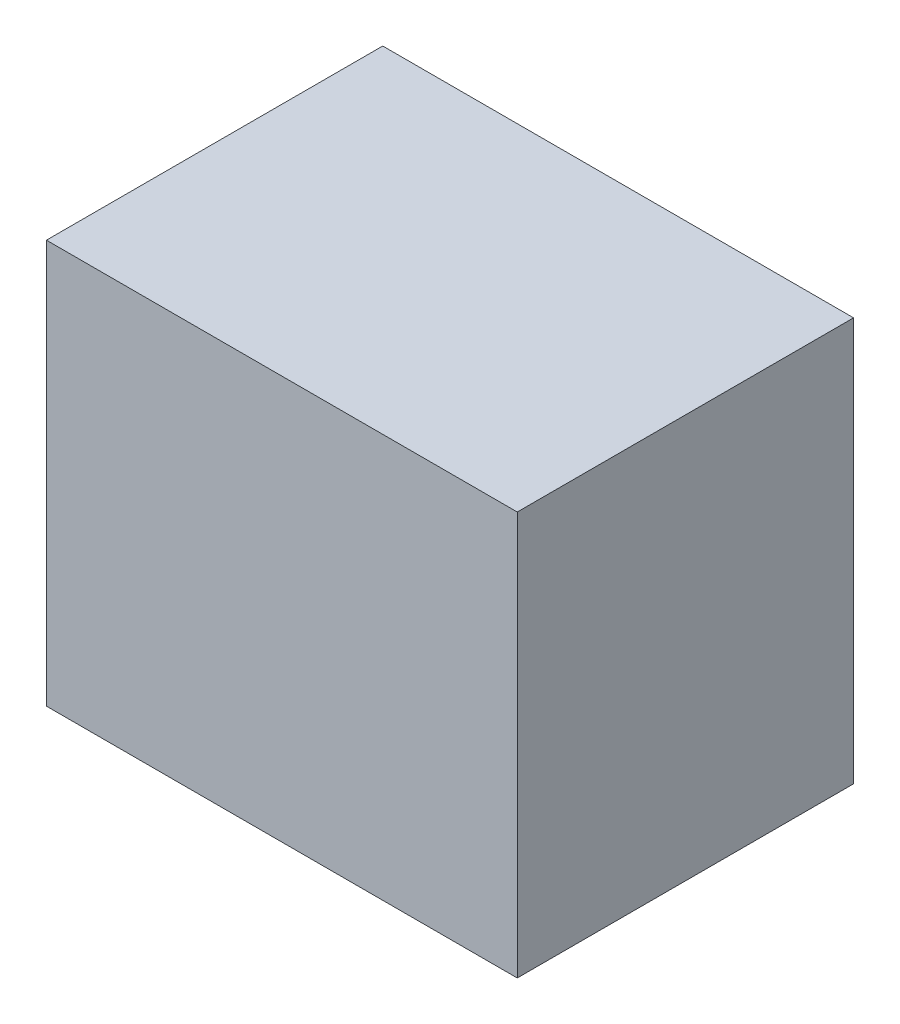
SolidWorks part; units mm, degrees
material "Alumina"
ref_plane "Front Plane" through (0, 0, 0) normal (0, 0, 1) x (1, 0, 0)
ref_plane "Top Plane" through (0, 0, 0) normal (0, 1, 0) x (1, 0, 0)
ref_plane "Right Plane" through (0, 0, 0) normal (1, 0, 0) x (0, 0, -1)
sketch "Sketch1" plane through (0, 0, 0) normal (0, 0, 1) x (1, 0, 0)
  line L1 (0, 0) -> (700, 0)
  line L2 (0, 0) -> (0, 600)
  line L3 (0, 600) -> (700, 600)
  line L4 (700, 0) -> (700, 600)
  dimension "Length" = 700
  dimension "Width" = 600
extrude "Boss-Extrude1" add sketch "Sketch1" along normal blind 500
shell "Shell1" [suppressed] thickness 20
shell "Shell2" [suppressed] thickness 20
shell "Shell3" [suppressed] thickness 20
shell "Shell4" thickness 20
shell "Shell5" [suppressed] thickness 20
